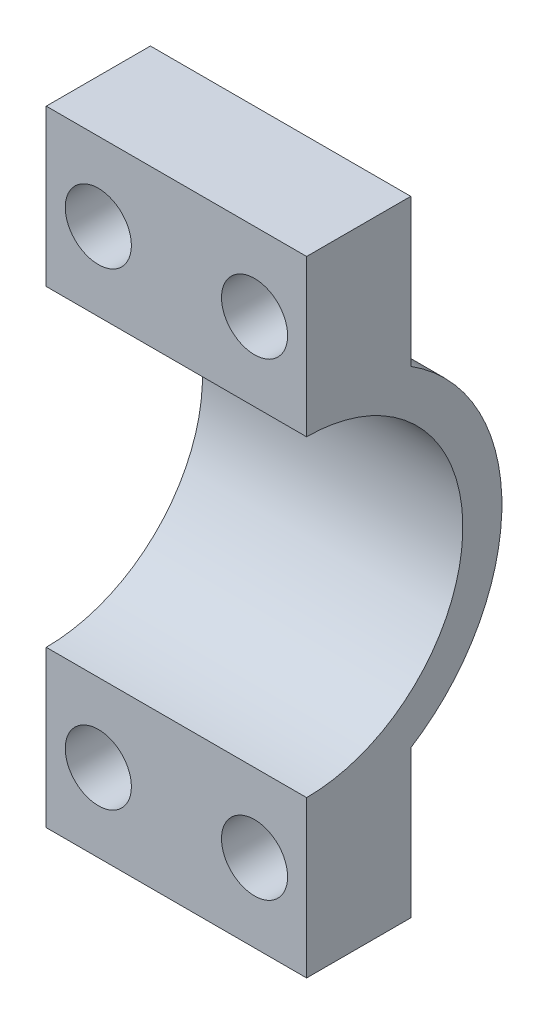
SolidWorks part; units mm, degrees
material "Cast Alloy Steel"
ref_plane "Front Plane" through (0, 0, 0) normal (0, 0, 1) x (1, 0, 0)
ref_plane "Top Plane" through (0, 0, 0) normal (0, 1, 0) x (1, 0, 0)
ref_plane "Right Plane" through (0, 0, 0) normal (1, 0, 0) x (0, 0, -1)
sketch "Sketch1" plane through (0, 0, 0) normal (1, 0, 0) x (0, 0, -1)
  line L0 (0, -30) -> (0, -60)
  line L1 (0, 60) -> (20, 60)
  line L2 (0, 60) -> (0, 30)
  line L3 (0, -60) -> (20, -60)
  line L4 (20, 60) -> (20, 31.7214)
  line L5 (20, -31.7214) -> (20, -60)
  arc A0 (0, -30) -> (0, 30) centre (0, 0) ccw
  arc A1 (20, -31.7214) -> (20, 31.7214) centre (0, 0) ccw
  dimension "D1" = 60
  dimension "D2" = 75
  dimension "D3" = 120
  dimension "D4" = 60
  dimension "D5" = 20
extrude "Boss-Extrude1" add sketch "Sketch1" along normal mid plane 50
hole_wizard "1/2 (0.5) Diameter Hole1" positions "Sketch2" profile "Sketch3" hole size "1/2" standard "ANSI Inch" end condition up to next
sketch "Sketch2" plane through (0, 0, 0) normal (0, 0, 1) x (1, 0, 0)
  point P0 (-15, 45)
  point P8 (15, 45)
  point P9 (15, -45)
  point P10 (-15, -45)
  dimension "D1" = 45
  dimension "D2" = 15
  dimension "D3" = 2
  dimension "D4" = 2
sketch "Sketch3" plane through (-15, 45, 0) normal (1, 0, 0) x (0, -1, 0)
  line L0 (0, 0) -> (0, 20)
  line L1 (0, 20) -> (6.35, 20)
  line L2 (6.35, 20) -> (6.35, 0)
  line L5 (6.35, 0) -> (0, 0)
  line L11 (0, -6.35) -> (0, 107.95) construction
  dimension "Thru Hole Dia." = 12.7
  dimension "Thru Hole Depth" = 20
